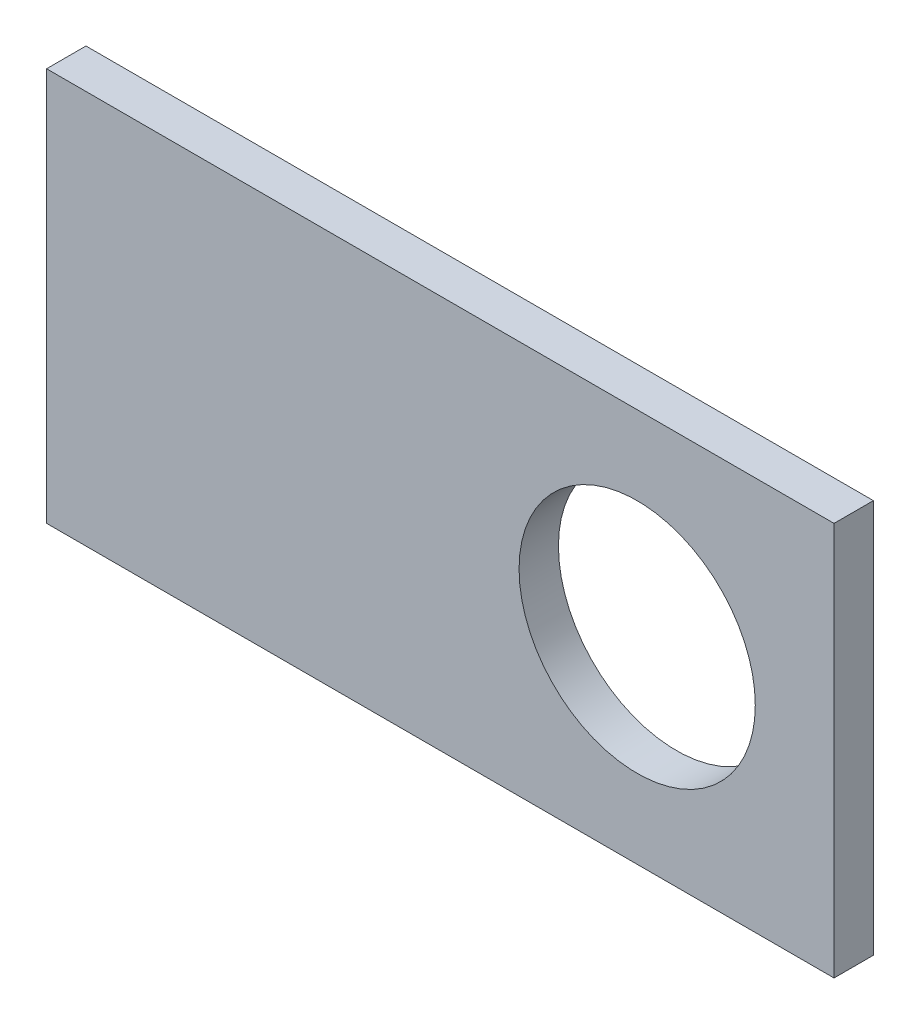
SolidWorks part; units mm, degrees
ref_plane "Front Plane" through (0, 0, 0) normal (0, 0, 1) x (1, 0, 0)
ref_plane "Top Plane" through (0, 0, 0) normal (0, 1, 0) x (1, 0, 0)
ref_plane "Right Plane" through (0, 0, 0) normal (1, 0, 0) x (0, 0, -1)
other "Configuration Table"
sketch "Sketch1" plane through (0, 0, 0) normal (0, 0, 1) x (1, 0, 0)
  line L1 (0, 0) -> (10000, 0)
  line L2 (0, 0) -> (0, 5000)
  line L3 (0, 5000) -> (10000, 5000)
  line L4 (10000, 0) -> (10000, 5000)
  circle A0 centre (7500, 2500) radius 1500
extrude "Boss-Extrude1" add sketch "Sketch1" along normal blind 500
ref_point "Point1"
